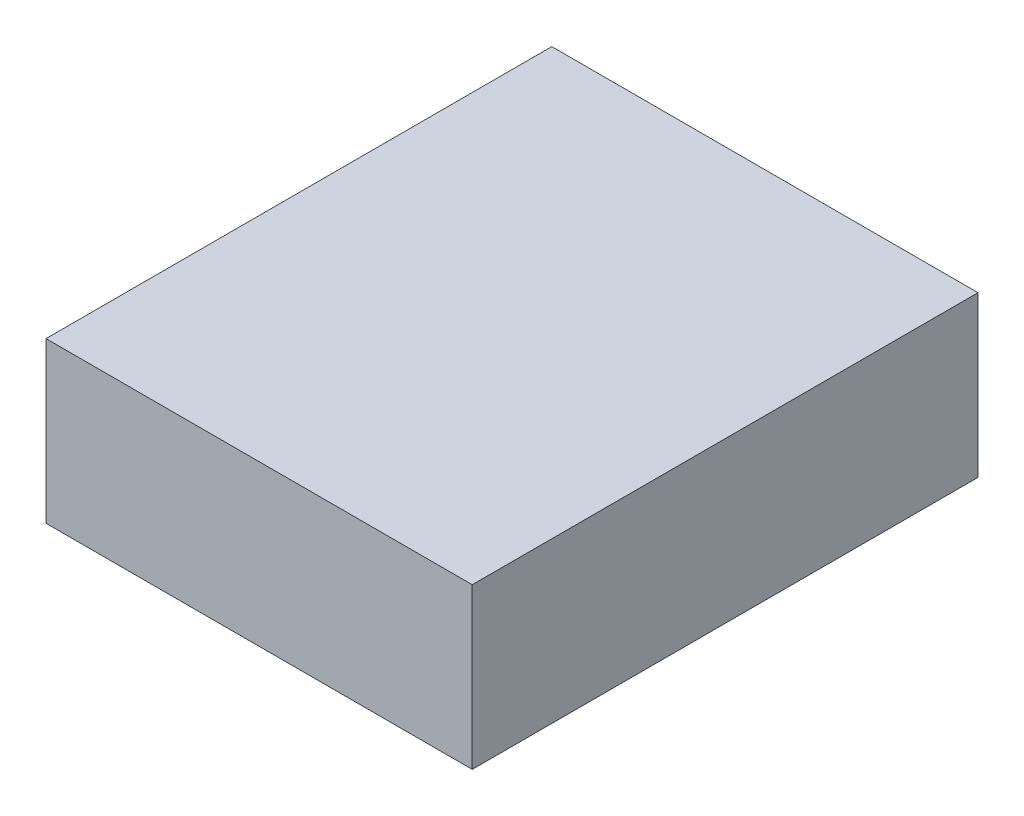
SolidWorks part; units mm, degrees
ref_plane "Front Plane" through (0, 0, 0) normal (0, 0, 1) x (1, 0, 0)
ref_plane "Top Plane" through (0, 0, 0) normal (0, 1, 0) x (1, 0, 0)
ref_plane "Right Plane" through (0, 0, 0) normal (1, 0, 0) x (0, 0, -1)
sketch "pilotSketch_base" plane through (0, 0, 0) normal (0, 1, 0) x (1, 0, 0)
  line L0 (-5, 5) -> (5, -5) construction
  line L1 (-5, -5) -> (5, 5) construction
  line L2 (0, 0) -> (6.6791, 0) construction
  point P5 (0, 0)
  dimension "D1" = 10
sketch "Sketch2" plane through (0, 0, 0) normal (0, 1, 0) x (1, 0, 0)
  line L0 (-0.9091, -0.9091) -> (-5, -5)
  line L1 (-5, -5) -> (5, -5)
  dimension "D1" = 45
ref_plane "motorSymmetryPlane" through (0, 0, 0) normal (0.7071, 0, 0.7071) x (-0.7071, 0, 0.7071)
sketch "pilotSketch_angle" plane through (0, 0, 0) normal (0.7071, 0, 0.7071) x (-0.7071, 0, 0.7071)
  line L0 (7.0711, 0) -> (1.6965, -3.103) construction
  line L4 (7.0711, 0) -> (-7.0711, 0) construction
  dimension "D1" = 30
ref_plane "motorMountPlane" through (-5, 0, 5) normal (0.6124, 0.5, -0.6124) x (0.7815, -0.5, 0.3732)
ref_plane "sideWall_mounting" through (0, 0, 5) normal (0, 0, 1) x (1, 0, 0)
ref_plane "sideWall_other" through (-5, 0, 0) normal (1, 0, 0) x (0, 0, -1)
sketch "Sketch1" plane through (0, 0, 0) normal (0, 1, 0) x (1, 0, 0)
  line L1 (-10.4778, 16.4005) -> (16.1702, 16.4005)
  line L2 (-10.4778, 16.4005) -> (-10.4778, -15.219)
  line L3 (-10.4778, -15.219) -> (16.1702, -15.219)
  line L4 (16.1702, 16.4005) -> (16.1702, -15.219)
extrude "pierceablePlane" add sketch "Sketch1" against normal blind 10
sketch3d "3DSketch1"
  line L0 (-2.1716, 19.0526, -7.7279) -> (15.5061, 0, -5.6066) construction
  line L1 (-2.1716, 19.0526, -7.7279) -> (7.7279, 19.0526, 2.1716)
  line L2 (-2.1716, 19.0526, -7.7279) -> (5.6066, 0, -15.5061)
  line L3 (5.6066, 0, -15.5061) -> (15.5061, 0, -5.6066)
  line L4 (7.7279, 19.0526, 2.1716) -> (15.5061, 0, -5.6066)
  line L5 (-5, 0, 5) -> (-1.1996, 3.103, 1.1996) construction
  point P4 (6.6673, 9.5263, -6.6673)
  point P7 (2.8437, 8.4481, 0.5712)
  point P8 (4.9533, 2.0546, -1.907)
  dimension "D1" = 22
  dimension "D2" = 14
equation "\"azimuthalAngle\"= 45deg"
equation "\"altidudeAngle\" = 30deg"
equation "\"polarAngle\"= 90deg - \"altidudeAngle\""
equation "\"D1@Sketch2\"=\"azimuthalAngle\""
equation "\"D1@pilotSketch_angle\"=\"altidudeAngle\""
